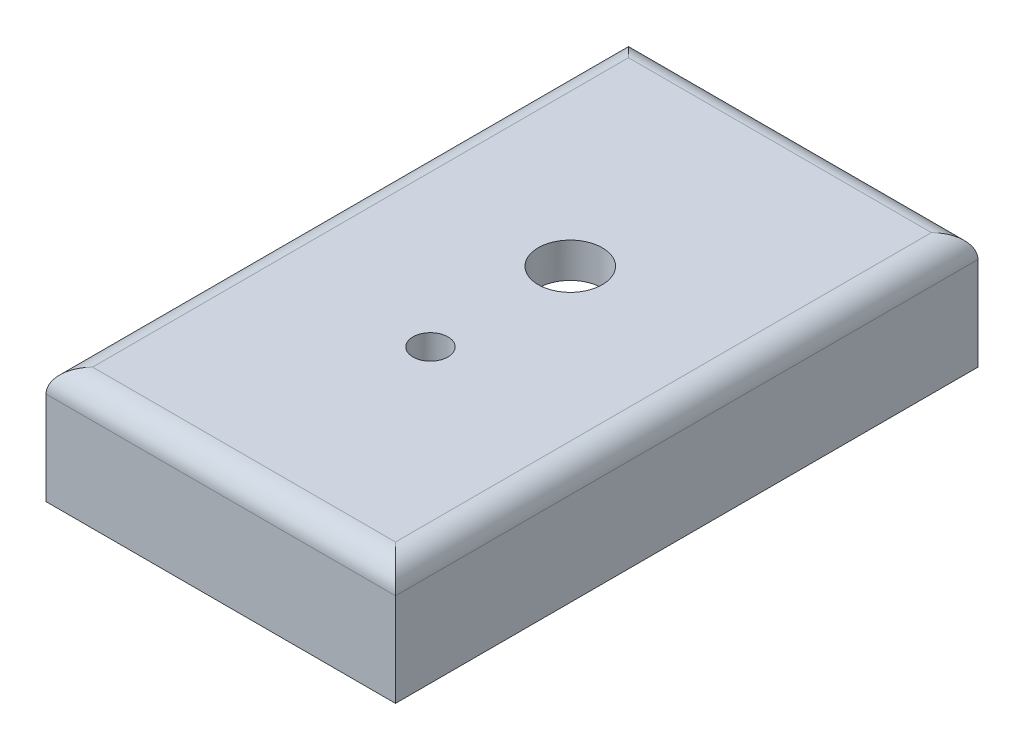
SolidWorks part; units mm, degrees
ref_plane "Front Plane" through (0, 0, 0) normal (0, 0, 1) x (1, 0, 0)
ref_plane "Top Plane" through (0, 0, 0) normal (0, 1, 0) x (1, 0, 0)
ref_plane "Right Plane" through (0, 0, 0) normal (1, 0, 0) x (0, 0, -1)
sketch "Sketch1" plane through (0, 0, 0) normal (0, 1, 0) x (1, 0, 0)
  line L1 (-15, -25) -> (15, -25)
  line L2 (-15, -25) -> (-15, 25)
  line L3 (-15, 25) -> (15, 25)
  line L4 (15, -25) -> (15, 25)
  line L5 (-15, -25) -> (15, 25) construction
  line L6 (-15, 25) -> (15, -25) construction
  point P0 (0, 0)
  dimension "D1" = 30
  dimension "D2" = 50
extrude "Boss-Extrude1" add sketch "Sketch1" along normal blind 10
shell "Shell1" thickness 3
sketch "Sketch2" plane through (0, 10, 0) normal (0, 1, 0) x (1, 0, 0)
  line L0 (0, 25) -> (0, -25) construction
  line L1 (15, 25) -> (-15, 25) construction
  line L2 (-15, -25) -> (15, -25) construction
  circle A0 centre (0, -7) radius 1.5
  circle A1 centre (0, 5) radius 2.75
  point P10 (0, 0)
  dimension "D1" = 3
  dimension "D2" = 18
  dimension "D3" = 12
  dimension "D5" = 5.5
extrude "Cut-Extrude1" cut sketch "Sketch2" against normal up to next
sketch "Sketch3" plane through (-15, 0, 0) normal (-1, 0, 0) x (0, 0, 1)
  line L0 (0, 0) -> (0, 10) construction
  line L1 (-25, 10) -> (25, 10) construction
  line L2 (-25, 0) -> (25, 0) construction
  line L3 (-10, 5) -> (10, 5)
  line L4 (-10, 5) -> (-10, 0)
  line L5 (-10, 0) -> (10, 0)
  line L6 (10, 5) -> (10, 0)
  line L7 (-10, 5) -> (10, 0) construction
  line L8 (-10, 0) -> (10, 5) construction
  point P5 (0, 2.5)
  dimension "D1" = 20
  dimension "D2" = 5
extrude "Cut-Extrude2" cut sketch "Sketch3" against normal up to next
fillet "Fillet1" radius 2 4 edges at (-13.5, 5, 10) (-13.5, 0, 10) (-13.5, 5, -10) (-13.5, 0, -10)
fillet "Fillet2" radius 2 4 edges at (0, 10, -25) (15, 10, 0) (-15, 10, 0) (0, 10, 25)
